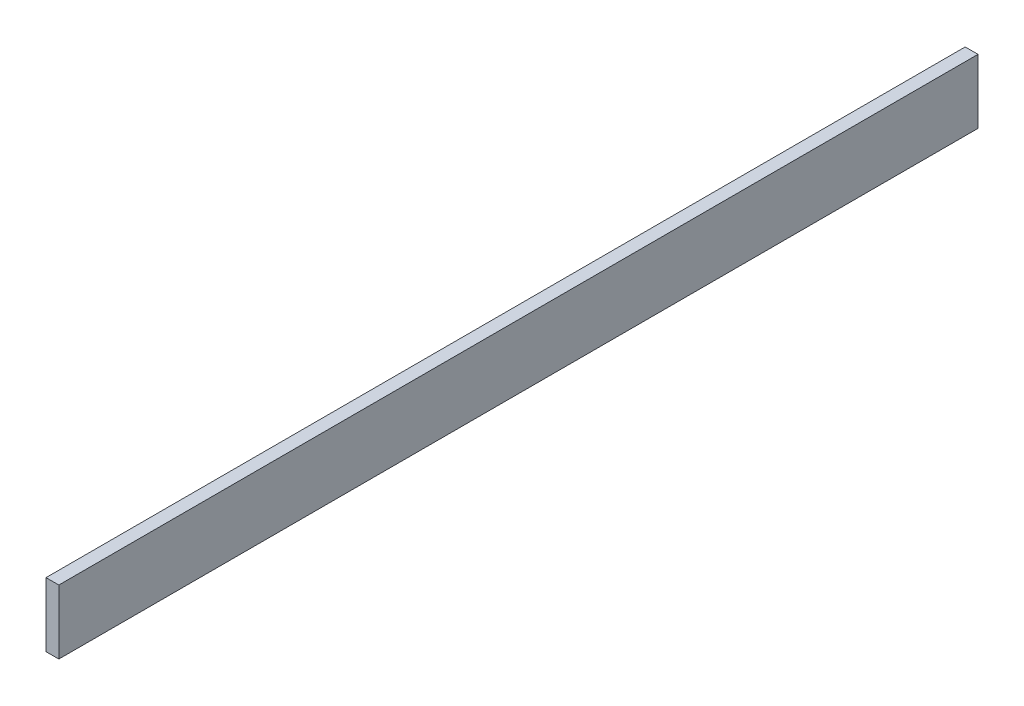
SolidWorks part; units mm, degrees
material "ASTM A36 Steel"
ref_plane "Front Plane" through (0, 0, 0) normal (0, 0, 1) x (1, 0, 0)
ref_plane "Top Plane" through (0, 0, 0) normal (0, 1, 0) x (1, 0, 0)
ref_plane "Right Plane" through (0, 0, 0) normal (1, 0, 0) x (0, 0, -1)
sketch "Sketch1" plane through (0, 0, 0) normal (1, 0, 0) x (0, 0, -1)
  line L1 (-107.5, -7.5) -> (107.5, -7.5)
  line L2 (-107.5, -7.5) -> (-107.5, 7.5)
  line L3 (-107.5, 7.5) -> (107.5, 7.5)
  line L4 (107.5, -7.5) -> (107.5, 7.5)
  line L5 (-107.5, -7.5) -> (107.5, 7.5) construction
  line L6 (-107.5, 7.5) -> (107.5, -7.5) construction
  point P0 (0, 0)
  dimension "D1" = 215
  dimension "D2" = 15
extrude "Boss-Extrude1" add sketch "Sketch1" along normal blind 3
